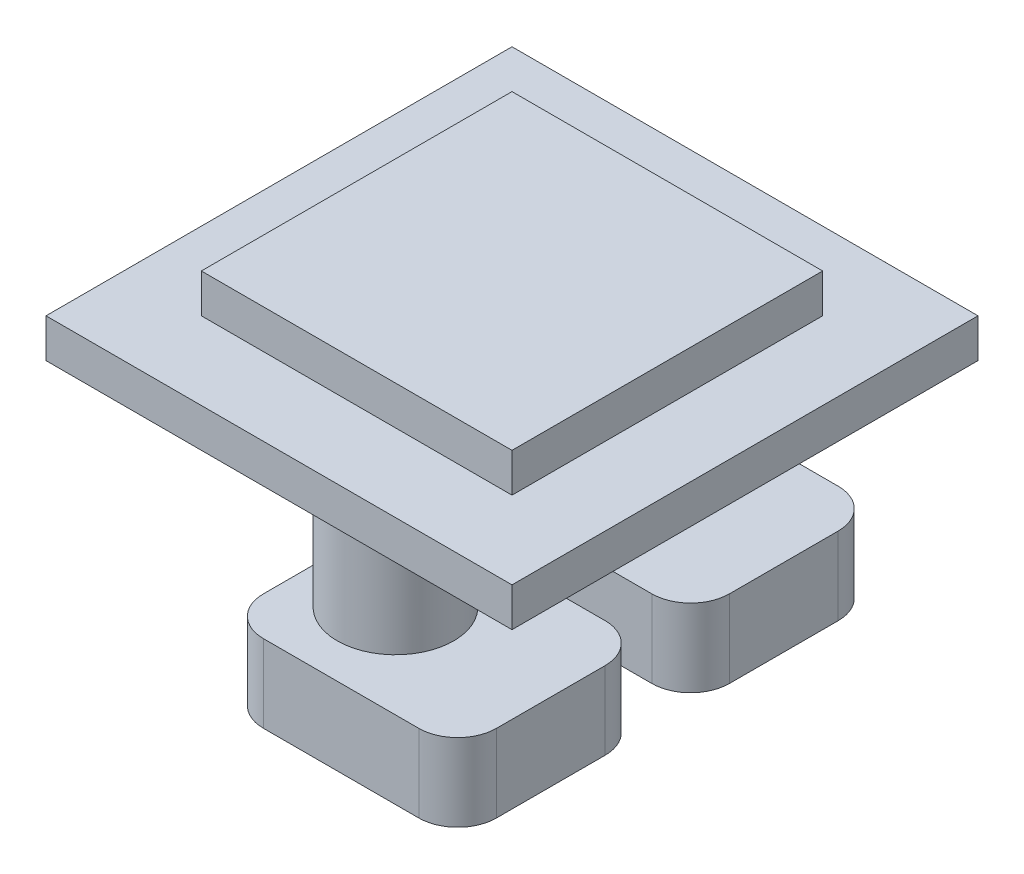
SolidWorks part; units mm, degrees
ref_plane "Front Plane" through (0, 0, 0) normal (0, 0, 1) x (1, 0, 0)
ref_plane "Top Plane" through (0, 0, 0) normal (0, 1, 0) x (1, 0, 0)
ref_plane "Right Plane" through (0, 0, 0) normal (1, 0, 0) x (0, 0, -1)
sketch "Sketch1" plane through (0, 0, 0) normal (0, 1, 0) x (1, 0, 0)
  line L1 (0, 0) -> (40, 0)
  line L2 (0, 0) -> (0, 40)
  line L3 (0, 40) -> (40, 40)
  line L4 (40, 0) -> (40, 40)
  dimension "D1" = 40
  dimension "D2" = 40
extrude "Boss-Extrude1" add sketch "Sketch1" along normal blind 5
sketch "Sketch2" plane through (0, 0, 0) normal (0, -1, 0) x (-1, 0, 0)
  line L0 (0, 40) -> (0, 0) construction
  line L1 (10, -10) -> (-50, -10)
  line L2 (10, -10) -> (10, 50)
  line L3 (10, 50) -> (-50, 50)
  line L4 (-50, -10) -> (-50, 50)
  line L5 (0, 0) -> (-40, 0) construction
  dimension "D1" = 60
  dimension "D2" = 60
  dimension "D3" = 10
  dimension "D4" = 10
extrude "Boss-Extrude2" add sketch "Sketch2" along normal blind 5
sketch "Sketch3" plane through (0, -5, 0) normal (0, -1, 0) x (-1, 0, 0)
  line L0 (-50, -10) -> (10, -10) construction
  line L1 (10, 50) -> (-50, 50) construction
  line L2 (-50, 50) -> (-50, -10) construction
  circle A0 centre (-20, 5) radius 7.5
  circle A1 centre (-20, 35) radius 7.5
  dimension "D1" = 15
  dimension "D2" = 15
  dimension "D3" = 15
  dimension "D4" = 30
  dimension "D5" = 30
  dimension "D6" = 15
extrude "Boss-Extrude3" add sketch "Sketch3" along normal blind 30
sketch "Sketch4" plane through (0, -35, 0) normal (0, -1, 0) x (-1, 0, 0)
  line L1 (-40, -7) -> (-10, -7)
  line L2 (-40, -7) -> (-40, 17)
  line L3 (-40, 17) -> (-10, 17)
  line L4 (-10, -7) -> (-10, 17)
  line L5 (-40, 23) -> (-10, 23)
  line L6 (-40, 23) -> (-40, 47)
  line L7 (-40, 47) -> (-10, 47)
  line L8 (-10, 23) -> (-10, 47)
  circle A0 centre (-20, 5) radius 7.5 construction
  circle A1 centre (-20, 35) radius 7.5 construction
  dimension "D2" = 12
  dimension "D1" = 12
  dimension "D3" = 10
  dimension "D4" = 20
  dimension "D5" = 12
  dimension "D6" = 12
  dimension "D7" = 20
  dimension "D8" = 10
extrude "Boss-Extrude5" add sketch "Sketch4" against normal blind 10
fillet "Fillet1" radius 5 8 edges at (10, -30, 7) (10, -30, -17) (10, -30, -23) (10, -30, -47) (40, -30, -47) (40, -30, -23) (40, -30, -17) (40, -30, 7)
